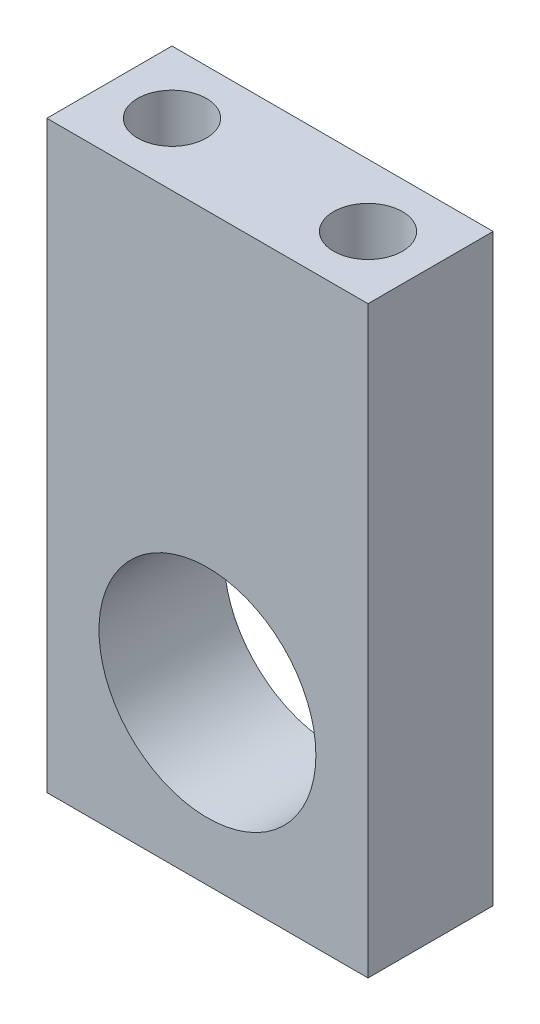
SolidWorks part; units mm, degrees
ref_plane "Front" through (0, 0, 0) normal (0, 0, 1) x (1, 0, 0)
ref_plane "Top" through (0, 0, 0) normal (0, 1, 0) x (1, 0, 0)
ref_plane "Right" through (0, 0, 0) normal (1, 0, 0) x (0, 0, -1)
sketch "Sketch1" plane through (0, 0, 0) normal (0, 1, 0) x (1, 0, 0)
  line L1 (-7.7, 3) -> (7.7, 3)
  line L2 (-7.7, 3) -> (-7.7, -3)
  line L3 (-7.7, -3) -> (7.7, -3)
  line L4 (7.7, 3) -> (7.7, -3)
  line L5 (-7.7, 3) -> (7.7, -3) construction
  line L6 (-7.7, -3) -> (7.7, 3) construction
  point P1 (0, 0)
  dimension "D1" = 6
  dimension "D2" = 15.4
extrude "Boss-Extrude1" add sketch "Sketch1" along normal blind 28
sketch "Sketch Reference for holes" plane through (0, 28, 0) normal (0, 1, 0) x (1, 0, 0)
  line L0 (0, 3) -> (0, -3) construction
  line L1 (7.7, 3) -> (-7.7, 3) construction
  line L2 (-7.7, -3) -> (7.7, -3) construction
  line L7 (0, 0) -> (4.7, 0) construction
  line L8 (-4.7, 0) -> (0, 0) construction
  point P7 (0, 0)
  point P12 (0, 3)
  dimension "D1" = 4.7
hole_wizard "Tap Drill for M4x0.7 Tap1" positions "3DSketch1" profile "Sketch3" hole size "M4x0.7" standard "ANSI Metric"
sketch3d "3DSketch1"
  point P0 (-4.7, 28, 0)
  point P3 (4.7, 28, 0)
sketch "Sketch3" plane through (-4.7, 28, 0) normal (1, 0, 0) x (0, 0, 1)
  line L0 (0, 0) -> (0, 14.3914)
  line L1 (0, 14.3914) -> (1.65, 13.4)
  line L2 (1.65, 13.4) -> (1.65, 0)
  line L5 (1.65, 0) -> (0, 0)
  line L10 (0, 14.3914) -> (-1.65, 13.4) construction
  line L11 (0, -6.35) -> (0, 107.95) construction
  dimension "Hole Dia." = 3.3
  dimension "Hole Depth" = 13.4
  dimension "Drill Angle" = 118
sketch "Sketch4" plane through (0, 0, 3) normal (0, 0, 1) x (1, 0, 0)
  line L0 (0, 28) -> (0, 8) construction
  line L1 (-7.7, 28) -> (7.7, 28) construction
  circle A0 centre (0, 8) radius 5.2
  dimension "D2" = 10.4
  dimension "D1" = 20
extrude "Cut-Extrude Press Fit hole for solenoid tube" cut sketch "Sketch4" against normal up to next
hole_wizard "Tap Drill for M4x0.7 Tap2" positions "Sketch5" profile "Sketch6" hole size "M4x0.7" standard "ANSI Metric"
sketch "Sketch5" plane through (0, 0, 0) normal (0, -1, 0) x (-1, 0, 0)
  point P0 (-4.7, 0)
  point P3 (4.7, 0)
sketch "Sketch6" plane through (4.7, 0, 0) normal (1, 0, 0) x (0, 0, -1)
  line L0 (0, 0) -> (0, 3.9914)
  line L1 (0, 3.9914) -> (1.65, 3)
  line L2 (1.65, 3) -> (1.65, 0)
  line L5 (1.65, 0) -> (0, 0)
  line L10 (0, 3.9914) -> (-1.65, 3) construction
  line L11 (0, -6.35) -> (0, 107.95) construction
  dimension "Hole Dia." = 3.3
  dimension "Hole Depth" = 3
  dimension "Drill Angle" = 118
